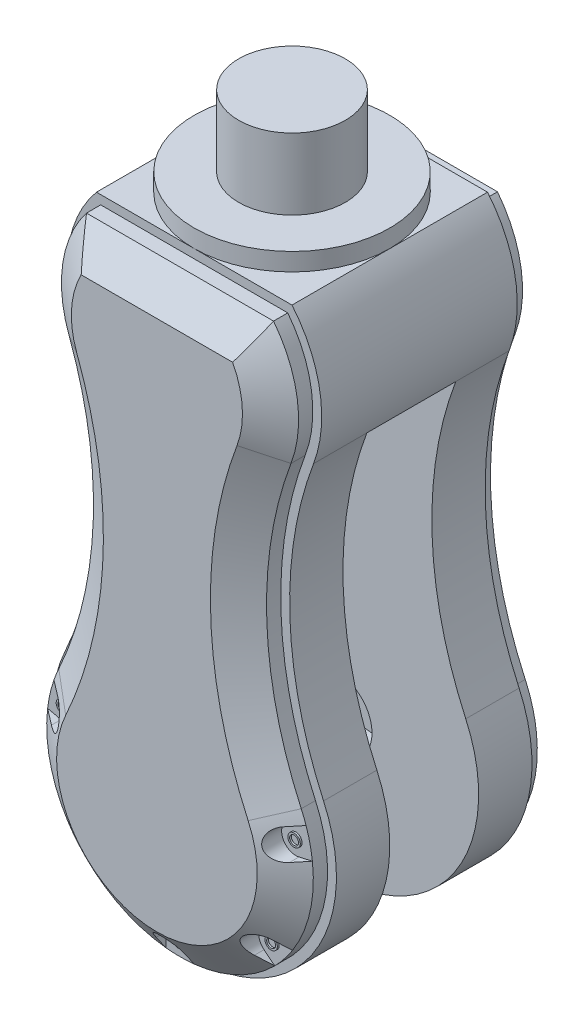
SolidWorks part; units mm, degrees
ref_plane "Front Plane" through (0, 0, 0) normal (0, 0, 1) x (1, 0, 0)
ref_plane "Top Plane" through (0, 0, 0) normal (0, 1, 0) x (1, 0, 0)
ref_plane "Right Plane" through (0, 0, 0) normal (1, 0, 0) x (0, 0, -1)
sketch "Sketch2" plane through (0, 0, 0) normal (0, 1, 0) x (1, 0, 0)
  circle A0 centre (0, 0) radius 27.5
  dimension "D1" = 55
extrude "Boss-Extrude1" add sketch "Sketch2" along normal blind 5
ref_plane "Plane1" through (0, 0, 27.5) normal (0, 0, -1) x (-1, 0, 0)
sketch "Sketch4" plane through (0, 0, 27.5) normal (0, 0, -1) x (-1, 0, 0)
  line L3 (-27.5, 0) -> (27.5, 0)
  line L4 (-27.5, 0) -> (27.5, 0) construction
  line L5 (27.5, 0) -> (27.5, 5) construction
  arc A1 (33.5593, -35.6104) -> (27.5, 0) centre (0, -23) ccw
  arc A2 (-36.3734, -116.3574) -> (36.3734, -116.3574) centre (0, -133) ccw
  arc A3 (33.5593, -35.6104) -> (36.3734, -116.3574) centre (132.0034, -72.6021) ccw
  arc A4 (-33.5593, -35.6104) -> (-36.3734, -116.3574) centre (-132.0034, -72.6021) cw
  arc A5 (-27.5, 0) -> (-33.5593, -35.6104) centre (0, -23) ccw
  dimension "D3" = 80
  dimension "D2" = 110
extrude "Boss-Extrude2" add sketch "Sketch4" along normal blind 15
sketch "Sketch5" plane through (0, 0, 27.5) normal (0, 0, 1) x (1, 0, 0)
  line L4 (26.3059, -2.5) -> (0, -2.5)
  line L5 (0, -2.5) -> (-26.3059, -2.5)
  line L6 (26.3059, -2.5) -> (0, -2.5)
  line L7 (0, -2.5) -> (-26.3059, -2.5)
  arc A10 (31.2191, -34.731) -> (26.3059, -2.5) centre (0, -23) ccw
  arc A11 (-26.3059, -2.5) -> (-31.2191, -34.731) centre (0, -23) ccw
  arc A12 (-34.1001, -117.3976) -> (-31.2191, -34.731) centre (-132.0034, -72.6021) ccw
  arc A13 (-34.1001, -117.3976) -> (34.1001, -117.3976) centre (0, -133) ccw
  arc A14 (31.2191, -34.731) -> (34.1001, -117.3976) centre (132.0034, -72.6021) ccw
  arc A15 (31.2191, -34.731) -> (26.3059, -2.5) centre (0, -23) ccw
  arc A16 (-26.3059, -2.5) -> (-31.2191, -34.731) centre (0, -23) ccw
  arc A17 (-34.1001, -117.3976) -> (-31.2191, -34.731) centre (-132.0034, -72.6021) ccw
  arc A18 (-34.1001, -117.3976) -> (34.1001, -117.3976) centre (0, -133) ccw
  arc A19 (31.2191, -34.731) -> (34.1001, -117.3976) centre (132.0034, -72.6021) ccw
  dimension "D1" = 2.5
extrude "Boss-Extrude3" add sketch "Sketch5" along normal blind 4
sketch "Sketch7" plane through (0, 0, 31.5) normal (0, 0, 1) x (1, 0, 0)
  line L1 (26.3059, -2.5) -> (-26.3059, -2.5)
  line L2 (26.3059, -2.5) -> (-26.3059, -2.5)
  arc A5 (31.2191, -34.731) -> (34.1001, -117.3976) centre (132.0034, -72.6021) ccw
  arc A6 (31.2191, -34.731) -> (26.3059, -2.5) centre (0, -23) ccw
  arc A7 (-26.3059, -2.5) -> (-31.2191, -34.731) centre (0, -23) ccw
  arc A8 (-34.1001, -117.3976) -> (-31.2191, -34.731) centre (-132.0034, -72.6021) ccw
  arc A9 (-34.1001, -117.3976) -> (34.1001, -117.3976) centre (0, -133) ccw
  arc A10 (31.2191, -34.731) -> (34.1001, -117.3976) centre (132.0034, -72.6021) ccw
  arc A11 (31.2191, -34.731) -> (26.3059, -2.5) centre (0, -23) ccw
  arc A12 (-26.3059, -2.5) -> (-31.2191, -34.731) centre (0, -23) ccw
  arc A13 (-34.1001, -117.3976) -> (-31.2191, -34.731) centre (-132.0034, -72.6021) ccw
  arc A14 (-34.1001, -117.3976) -> (34.1001, -117.3976) centre (0, -133) ccw
  dimension "D1" = 0
extrude "Boss-Extrude4" add sketch "Sketch7" along normal blind 6.5 draft 55
sketch "Sketch9" plane through (0, 0, 38) normal (0, 0, 1) x (1, 0, 0)
  line L0 (0, 0) -> (0, -182.0486) construction
  line L1 (0, -170.4185) -> (0, -166.4185)
  line L2 (4, -166.4185) -> (4, -173.9179)
  line L3 (4, -173.9179) -> (-4, -173.9179)
  line L4 (-4, -173.9179) -> (-4, -166.4185)
  arc A4 (4, -166.4185) -> (-4, -166.4185) centre (0, -166.4185) ccw
  dimension "D1" = 4
extrude "Cut-Extrude1" cut sketch "Sketch9" against normal blind 6.5 contours L0 A4 L4 L3 L1 | A4 L0 L1 L3 L2
sketch "Sketch10" plane through (0, 0, 31.5) normal (0, 0, 1) x (1, 0, 0)
  circle A0 centre (0, -166.4185) radius 1.75
  circle A1 centre (0, -166.4185) radius 1.25
  dimension "D1" = 3.5
  dimension "D2" = 2.5
extrude "Boss-Extrude5" add sketch "Sketch10" along normal blind 0.5
pattern_circular "CirPattern1" count 7 over 360 about axis through (0, -133, 0) along (0, 0, 1) skipping 3, 4 of "Cut-Extrude1", "Boss-Extrude5"
sketch "Sketch11" plane through (0, 0, 12.5) normal (0, 0, -1) x (-1, 0, 0)
  line L0 (-33.5593, -35.6104) -> (33.5593, -35.6104)
  line L1 (24.4949, 0) -> (-24.4949, 0) construction
  line L2 (24.4949, 0) -> (-24.4949, 0)
  line L3 (-24.4949, 0) -> (-27.5, 0)
  line L4 (24.4949, 0) -> (27.5, 0)
  arc A0 (33.5593, -35.6104) -> (27.5, 0) centre (0, -23) ccw construction
  arc A1 (-27.5, 0) -> (-33.5593, -35.6104) centre (0, -23) ccw construction
  arc A2 (33.5593, -35.6104) -> (27.5, 0) centre (0, -23) ccw
  arc A3 (-27.5, 0) -> (-33.5593, -35.6104) centre (0, -23) ccw
extrude "Boss-Extrude6" add sketch "Sketch11" along normal blind 40
mirror "Mirror2" about plane through (0, 0, 0) normal (0, 0, 1) of "CirPattern1", "Boss-Extrude5", "Cut-Extrude1", "Boss-Extrude4", "Boss-Extrude3", "Boss-Extrude2"
sketch "Sketch12" plane through (0, 5, 0) normal (0, 1, 0) x (1, 0, 0)
  circle A0 centre (0, 0) radius 15
  dimension "D1" = 30
extrude "Boss-Extrude7" add sketch "Sketch12" along normal blind 20
sketch "Sketch13" plane through (0, 0, -12.5) normal (0, 0, 1) x (1, 0, 0)
  circle A0 centre (0, -133) radius 10
  dimension "D1" = 20
extrude "Cut-Extrude2" cut sketch "Sketch13" against normal blind 10
mirror "Mirror3" about plane through (0, 0, 0) normal (0, 0, 1) of "Cut-Extrude2"
